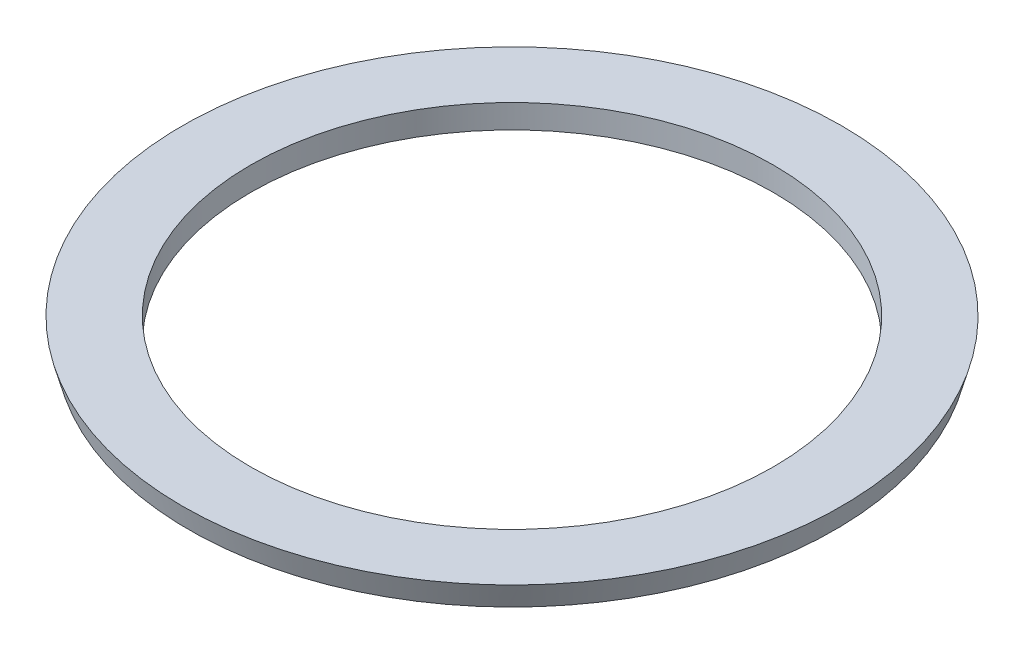
SolidWorks part; units mm, degrees
ref_plane "Front Plane" through (0, 0, 0) normal (0, 0, 1) x (1, 0, 0)
ref_plane "Top Plane" through (0, 0, 0) normal (0, 1, 0) x (1, 0, 0)
ref_plane "Right Plane" through (0, 0, 0) normal (1, 0, 0) x (0, 0, -1)
sketch "Sketch1" plane through (0, 0, 0) normal (0, 0, 1) x (1, 0, 0)
  line L0 (0, 0) -> (0, 100) construction
  line L1 (22, 33.8) -> (27.181, 33.8)
  line L2 (27.181, 33.8) -> (27.7328, 35.8)
  line L3 (27.7328, 35.8) -> (22, 35.8)
  line L4 (22, 35.8) -> (22, 33.8)
revolve "Taper clamp ring" add sketch "Sketch1" angle 360 about L0
